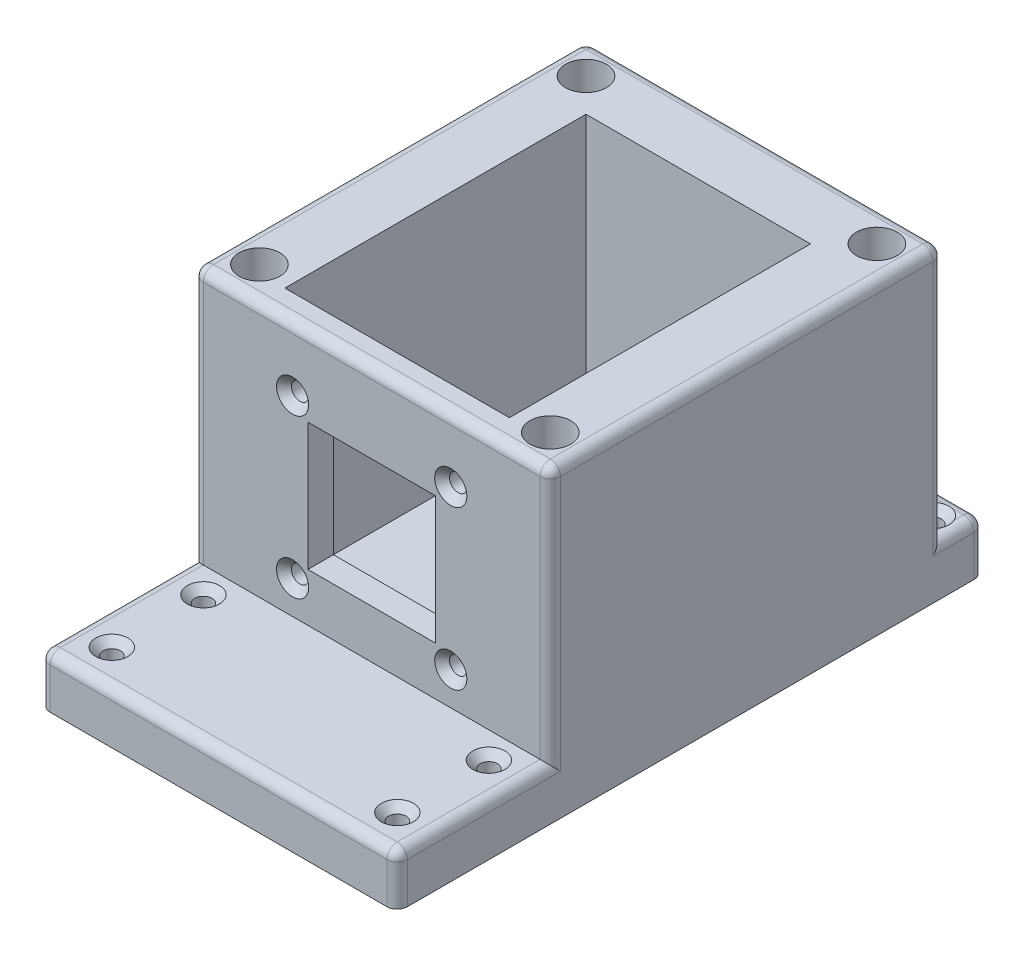
SolidWorks part; units mm, degrees
ref_plane "Front Plane" through (0, 0, 0) normal (0, 0, 1) x (1, 0, 0)
ref_plane "Top Plane" through (0, 0, 0) normal (0, 1, 0) x (1, 0, 0)
ref_plane "Right Plane" through (0, 0, 0) normal (1, 0, 0) x (0, 0, -1)
sketch "Sketch2" plane through (0, 0, 0) normal (0, 1, 0) x (1, 0, 0)
  line L1 (-35, 65) -> (35, 65)
  line L2 (-35, 65) -> (-35, -50)
  line L3 (-35, -50) -> (35, -50)
  line L4 (35, 65) -> (35, -50)
  point P0 (0, 0)
  dimension "D1" = 70
  dimension "D2" = 115
extrude "Boss-Extrude1" add sketch "Sketch2" along normal blind 10
sketch "Sketch8" plane through (0, 10, 0) normal (0, 1, 0) x (1, 0, 0)
  line L0 (35, -50) -> (35, 65) construction
  line L1 (-35, 65) -> (35, 65)
  line L2 (-35, 65) -> (-35, -20)
  line L3 (-35, -20) -> (35, -20)
  line L4 (35, 65) -> (35, -20)
  line L5 (-35, -15) -> (35, -15) construction
  line L6 (-22, -20) -> (22, -20)
  line L7 (-22, -20) -> (-22, 65) construction
  line L8 (22, -20) -> (22, 65) construction
  line L9 (-35, 57) -> (35, 57) construction
  line L11 (-35, 57) -> (35, 57)
  line L12 (-35, 57) -> (-35, 44)
  line L13 (-35, 44) -> (35, 44)
  line L14 (35, 57) -> (35, 44)
  line L15 (-35, 57) -> (-22, 57)
  line L16 (-35, 57) -> (-35, -20)
  line L17 (-35, -20) -> (-22, -20)
  line L18 (-22, 57) -> (-22, -20)
  line L19 (35, 57) -> (22, 57)
  line L20 (35, 57) -> (35, -20)
  line L21 (35, -20) -> (22, -20)
  line L22 (22, 57) -> (22, -20)
  line L23 (-35, -15) -> (35, -15)
  line L24 (-35, -15) -> (-35, -20)
  line L25 (-35, -20) -> (35, -20)
  line L26 (35, -15) -> (35, -20)
  point P9 (0, -20)
  point P10 (0, -15)
  point P14 (0, -20)
  point P18 (0, 65)
  point P19 (0, 57)
  dimension "D2" = 5
  dimension "D3" = 44
  dimension "D4" = 13
  dimension "D5" = 8
  dimension "D6" = 13
extrude "Boss-Extrude5" add sketch "Sketch8" along normal blind 50 contours L18 L11 L2 L13 | L22 L11 L18 L13 | L11 L22 L13 L4 | L22 L23 L20 L13 | L23 L22 L3 L6 | L23 L18 L3 L22 | L23 L16 L3 L18 | L8 L23 L18 L13
sketch "Sketch9" plane through (0, 60, 0) normal (0, 1, 0) x (1, 0, 0)
  circle A0 centre (-28.5, 50.5) radius 4
  circle A1 centre (28.5, 50.5) radius 4
  circle A2 centre (28.5, -13.5) radius 4
  circle A3 centre (-28.5, -13.5) radius 4
  dimension "D3" = 8
  dimension "D1" = 64
  dimension "D2" = 64
extrude "Cut-Extrude1" cut sketch "Sketch9" against normal blind 50
sketch "Sketch10" plane through (0, 0, 15) normal (0, 0, -1) x (-1, 0, 0)
  line L0 (22, 60) -> (22, 10) construction
  line L5 (-22, 54) -> (22, 10) construction
  line L6 (-22, 10) -> (22, 54) construction
  line L8 (-12.5, 44.5) -> (12.5, 44.5)
  line L9 (-12.5, 44.5) -> (-12.5, 19.5)
  line L10 (-12.5, 19.5) -> (12.5, 19.5)
  line L11 (12.5, 44.5) -> (12.5, 19.5)
  line L12 (-12.5, 44.5) -> (12.5, 19.5) construction
  line L13 (-12.5, 19.5) -> (12.5, 44.5) construction
  point P7 (0, 32)
  dimension "D1" = 44
  dimension "D2" = 25
extrude "Cut-Extrude2" cut sketch "Sketch10" against normal up to next
sketch "Sketch11" plane through (0, 0, 15) normal (0, 0, -1) x (-1, 0, 0)
  line L0 (12.5, 44.5) -> (-12.5, 19.5) construction
  line L1 (-12.5, 19.5) -> (-12.5, 44.5) construction
  line L2 (-12.5, 44.5) -> (12.5, 19.5) construction
sketch "Sketch13" plane through (0, 0, 15) normal (0, 0, -1) x (-1, 0, 0)
  line L0 (12.5, 44.5) -> (-12.5, 19.5) construction
  line L1 (-15.5, 47.5) -> (15.5, 47.5)
  line L2 (-15.5, 47.5) -> (-15.5, 16.5)
  line L3 (-15.5, 16.5) -> (15.5, 16.5)
  line L4 (15.5, 47.5) -> (15.5, 16.5)
  line L5 (-15.5, 47.5) -> (15.5, 16.5) construction
  line L6 (-15.5, 16.5) -> (15.5, 47.5) construction
  point P0 (0, 32)
  dimension "D1" = 31
  dimension "D2" = 31
hole_wizard "CSK for M3 Countersunk Flat Head Screw1" positions "Sketch14" profile "Sketch15" countersink size "M3" standard "DIN"
sketch "Sketch14" plane through (0, 0, 20) normal (0, 0, 1) x (1, 0, 0)
  point P0 (-15.5, 47.5)
  point P3 (15.5, 47.5)
  point P6 (15.5, 16.5)
  point P9 (-15.5, 16.5)
sketch "Sketch15" plane through (-15.5, 47.5, 20) normal (1, 0, 0) x (0, -1, 0)
  line L0 (0, 0) -> (0, 5)
  line L1 (0, 5) -> (1.7, 5)
  line L2 (1.7, 5) -> (1.7, 1.45)
  line L3 (1.7, 1.45) -> (3.15, 0)
  line L5 (3.15, 0) -> (0, 0)
  line L6 (-1.7, 1.45) -> (-3.15, 0) construction
  line L11 (0, -6.35) -> (0, 107.95) construction
  dimension "Thru Hole Dia." = 3.4
  dimension "Thru Hole Depth" = 5
  dimension "Near C'Sink Dia." = 6.3
  dimension "Near C'Sink Angle" = 90
fillet "Fillet1" radius 2 18 edges at (35, 5, 50) (-35, 5, 50) (-35, 5, -65) (35, 5, -65) (35, 35, 20) (35, 10, 35) (0, 10, 50) (-35, 35, 20) (-35, 10, 35) (0, 60, 20) (35, 60, -18.5) (35, 10, -61) (35, 35, -57) (0, 10, -65) (-35, 10, -61) (0, 60, -57) (-35, 35, -57) (-35, 60, -18.5)
sketch "Sketch16" plane through (0, 10, 0) normal (0, 1, 0) x (1, 0, 0)
  line L0 (-33, -20) -> (-33, -48) construction
  line L1 (-28, -25) -> (28, -25)
  line L2 (-28, -25) -> (-28, -43)
  line L3 (-28, -43) -> (28, -43)
  line L4 (28, -25) -> (28, -43)
  line L5 (-33, -48) -> (33, -48) construction
  line L6 (33, -48) -> (33, -20) construction
  line L7 (-33, -20) -> (33, -20) construction
  line L8 (33, 63) -> (-33, 63) construction
  line L9 (-33, 63) -> (-27, 63)
  line L10 (-33, 63) -> (-33, 57)
  line L11 (-33, 57) -> (-27, 57)
  line L12 (-27, 63) -> (-27, 57)
  line L13 (33, 63) -> (27, 63)
  line L14 (33, 63) -> (33, 57)
  line L15 (33, 57) -> (27, 57)
  line L16 (27, 63) -> (27, 57)
  line L17 (-33, 57) -> (33, 57) construction
  line L18 (-33, 63) -> (-33, 57) construction
  line L19 (33, 57) -> (33, 63) construction
  line L20 (-32.9771, 62.9974) -> (-26.9644, 56.9993) construction
  line L21 (-26.9936, 62.9974) -> (-32.9771, 56.9554) construction
  line L22 (33.0159, 62.9786) -> (26.9966, 56.9592) construction
  line L23 (27.0407, 62.9565) -> (33.0159, 57.0033) construction
  dimension "D1" = 5
  dimension "D2" = 5
  dimension "D3" = 5
  dimension "D4" = 5
  dimension "D5" = 0
  dimension "D6" = 0
  dimension "D7" = 0
  dimension "D8" = 0
  dimension "D9" = 0
hole_wizard "CSK for M3 Countersunk Flat Head Screw2" positions "Sketch17" profile "Sketch18" countersink size "M3" standard "DIN"
sketch "Sketch17" plane through (0, 10, 0) normal (0, 1, 0) x (1, 0, 0)
  point P0 (-29.899, 59.9147)
  point P2 (30.0949, 59.8896)
  point P4 (-27.9245, -25.0457)
  point P6 (28.1109, -25.1419)
  point P8 (28.0342, -43.001)
  point P10 (-27.996, -42.9244)
sketch "Sketch18" plane through (-29.899, 10, -59.9147) normal (1, 0, 0) x (0, 0, 1)
  line L0 (0, 0) -> (0, 31.0215)
  line L1 (0, 31.0215) -> (1.7, 30)
  line L2 (1.7, 30) -> (1.7, 1.45)
  line L3 (1.7, 1.45) -> (3.15, 0)
  line L5 (3.15, 0) -> (0, 0)
  line L6 (-1.7, 1.45) -> (-3.15, 0) construction
  line L10 (0, 31.0215) -> (-1.7, 30) construction
  line L11 (0, -6.35) -> (0, 107.95) construction
  dimension "Hole Dia." = 3.4
  dimension "Hole Depth" = 30
  dimension "Near C'Sink Dia." = 6.3
  dimension "Near C'Sink Angle" = 90
  dimension "Drill Angle" = 118
sketch "Sketch19" plane through (0, 10, 0) normal (0, 1, 0) x (1, 0, 0)
  line L0 (-22.2233, 43.9848) -> (21.8734, -14.8108) construction
  line L1 (21.8734, -14.8108) -> (22.2233, 43.9848) construction
  line L2 (22.2233, 43.9848) -> (-22.0483, -14.8108) construction
hole_wizard "CSK for M5 Countersunk Flat Head Screw2" positions "Sketch20" profile "Sketch21" countersink size "M5" standard "DIN"
sketch "Sketch20" plane through (0, 10, 0) normal (0, 1, 0) x (1, 0, 0)
  point P0 (0.175, 14.412)
sketch "Sketch21" plane through (0.175, 10, -14.412) normal (1, 0, 0) x (0, 0, 1)
  line L0 (0, 0) -> (0, 31.6524)
  line L1 (0, 31.6524) -> (2.75, 30)
  line L2 (2.75, 30) -> (2.75, 2.45)
  line L3 (2.75, 2.45) -> (5.2, 0)
  line L5 (5.2, 0) -> (0, 0)
  line L6 (-2.75, 2.45) -> (-5.2, 0) construction
  line L10 (0, 31.6524) -> (-2.75, 30) construction
  line L11 (0, -6.35) -> (0, 107.95) construction
  dimension "Hole Dia." = 5.5
  dimension "Hole Depth" = 30
  dimension "Near C'Sink Dia." = 10.4
  dimension "Near C'Sink Angle" = 90
  dimension "Drill Angle" = 118
